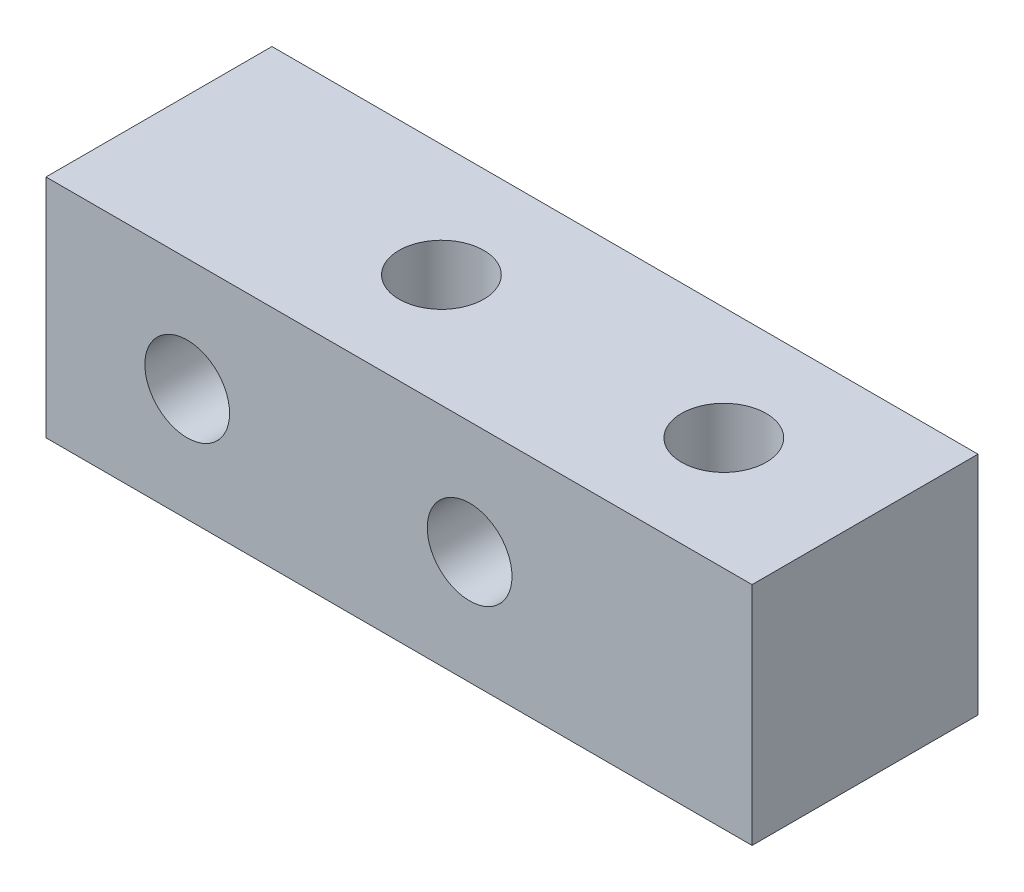
SolidWorks part; units mm, degrees
material "1345 合金"
ref_plane "前视基准面" through (0, 0, 0) normal (0, 0, 1) x (1, 0, 0)
ref_plane "上视基准面" through (0, 0, 0) normal (0, 1, 0) x (1, 0, 0)
ref_plane "右视基准面" through (0, 0, 0) normal (1, 0, 0) x (0, 0, -1)
other "Configuration Table"
sketch "草图1" plane through (0, 0, 0) normal (0, 1, 0) x (1, 0, 0)
  line L1 (-12.5, -4) -> (12.5, -4)
  line L2 (-12.5, -4) -> (-12.5, 4)
  line L3 (-12.5, 4) -> (12.5, 4)
  line L4 (12.5, -4) -> (12.5, 4)
  line L5 (-12.5, -4) -> (12.5, 4) construction
  line L6 (-12.5, 4) -> (12.5, -4) construction
  point P0 (0, 0)
  dimension "D1" = 25
  dimension "D2" = 8
extrude "凸台-拉伸1" add sketch "草图1" along normal blind 8
sketch "草图2" plane through (0, 8, 0) normal (0, 1, 0) x (1, 0, 0)
  line L0 (-13.8384, 0) -> (16.0597, 0) construction
  line L1 (12.5, -4) -> (12.5, 4) construction
  circle A0 centre (7.5, 0) radius 1.5
  circle A1 centre (-2.5, 0) radius 1.5
  dimension "D1" = 3
  dimension "D2" = 3
  dimension "D3" = 5
  dimension "D4" = 10
extrude "切除-拉伸1" cut sketch "草图2" against normal up to surface (8 mm away) up to face at (0, 0, 0)
sketch "草图3" plane through (0, 0, 4) normal (0, 0, 1) x (1, 0, 0)
  line L0 (-12.5, 4) -> (12.5, 4) construction
  line L1 (-12.5, 8) -> (-12.5, 0) construction
  line L2 (12.5, 8) -> (12.5, 0) construction
  circle A0 centre (-7.5, 4) radius 1.5
  circle A1 centre (2.5, 4) radius 1.5
  dimension "D1" = 3
  dimension "D2" = 3
  dimension "D3" = 5
  dimension "D4" = 10
extrude "切除-拉伸2" cut sketch "草图3" against normal up to surface (8 mm away) up to face at (0, 4, -4)
